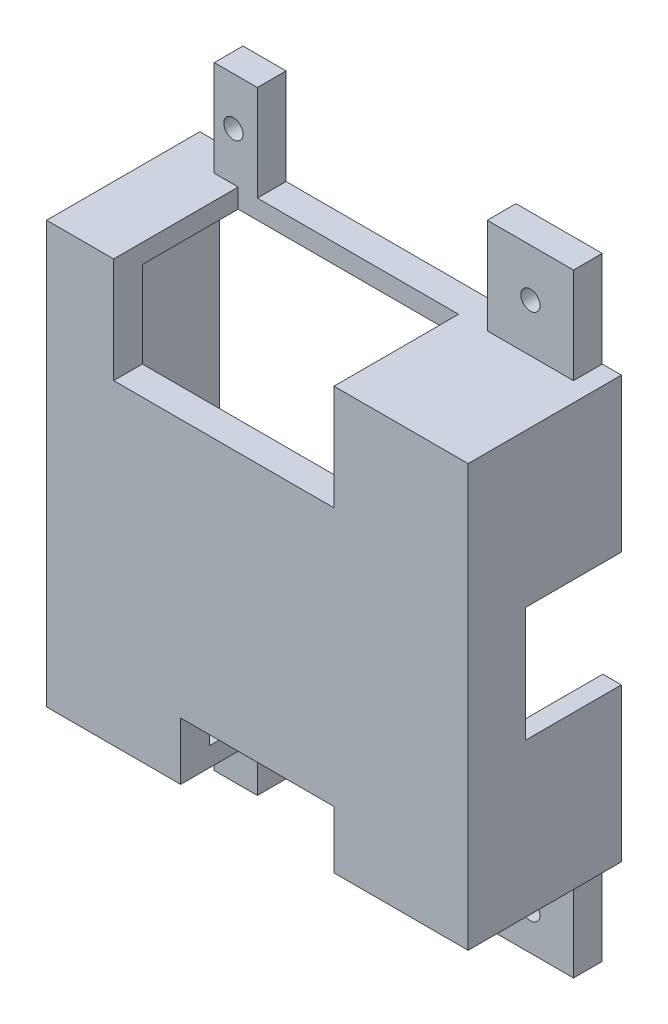
SolidWorks part; units mm, degrees
ref_plane "Front Plane" through (0, 0, 0) normal (0, 0, 1) x (1, 0, 0)
ref_plane "Top Plane" through (0, 0, 0) normal (0, 1, 0) x (1, 0, 0)
ref_plane "Right Plane" through (0, 0, 0) normal (1, 0, 0) x (0, 0, -1)
sketch "Sketch1" plane through (0, 0, 0) normal (0, 0, 1) x (1, 0, 0)
  line L0 (0, 0) -> (44, 0)
  line L1 (44, 0) -> (44, 44)
  line L2 (44, 44) -> (0, 44)
  line L3 (0, 44) -> (0, 0)
  dimension "D1" = 44
  dimension "D2" = 44
extrude "Boss-Extrude1" add sketch "Sketch1" along normal blind 16
sketch "Sketch3" plane through (0, 0, 0) normal (0, 0, -1) x (-1, 0, 0)
  line L1 (-42.0638, 42) -> (-2.0638, 42)
  line L2 (-42.0638, 42) -> (-42.0638, 2)
  line L3 (-42.0638, 2) -> (-2.0638, 2)
  line L4 (-2.0638, 42) -> (-2.0638, 2)
  dimension "D1" = 40
  dimension "D2" = 40
  dimension "D3" = 2
  dimension "D4" = 2
  dimension "D5" = 2
  dimension "D6" = 2
extrude "Cut-Extrude1" cut sketch "Sketch3" against normal blind 13
ref_plane "Plane1" through (0, 44, 16) normal (-1, 0, 0) x (0, 0, 1)
sketch "Sketch5" plane through (0, 0, 16) normal (0, 0, 1) x (1, 0, 0)
  line L0 (0, 44) -> (0, 0) construction
  line L1 (7, 44) -> (30, 44)
  line L2 (7, 44) -> (7, 33)
  line L3 (7, 33) -> (30, 33)
  line L4 (30, 44) -> (30, 33)
  dimension "D1" = 0
  dimension "D2" = 7
  dimension "D3" = 14
  dimension "D4" = 11
extrude "Cut-Extrude2" cut sketch "Sketch5" against normal blind 13
sketch "Sketch6" plane through (0, 0, 16) normal (0, 0, 1) x (1, 0, 0)
  line L0 (0, 0) -> (44, 0) construction
  line L1 (14, 6) -> (30, 6)
  line L2 (14, 6) -> (14, 0)
  line L3 (14, 0) -> (30, 0)
  line L4 (30, 6) -> (30, 0)
  dimension "D1" = 14
  dimension "D2" = 14
  dimension "D3" = 6
extrude "Cut-Extrude3" cut sketch "Sketch6" against normal blind 10
sketch "Sketch7" plane through (44, 0, 0) normal (1, 0, 0) x (0, 0, -1)
  line L0 (0, 0) -> (0, 44) construction
  line L1 (0, 16) -> (-10, 16)
  line L2 (0, 16) -> (0, 28)
  line L3 (0, 28) -> (-10, 28)
  line L4 (-10, 16) -> (-10, 28)
  dimension "D1" = 16
  dimension "D2" = 16
  dimension "D3" = 10
extrude "Cut-Extrude4" cut sketch "Sketch7" against normal blind 5
sketch "Sketch8" plane through (0, 0, 0) normal (0, -1, 0) x (-1, 0, 0)
  line L0 (0, 0) -> (-44, 0) construction
  line L1 (-4.5, -3) -> (-9, -3)
  line L2 (-4.5, -3) -> (-4.5, 0)
  line L3 (-4.5, 0) -> (-9, 0)
  line L4 (-9, -3) -> (-9, 0)
  line L6 (-33, -3) -> (-42, -3)
  line L7 (-33, -3) -> (-33, 0)
  line L8 (-33, 0) -> (-42, 0)
  line L9 (-42, -3) -> (-42, 0)
  dimension "D1" = 3
  dimension "D2" = 24
  dimension "D3" = 4.5
  dimension "D4" = 9
  dimension "D5" = 3
  dimension "D6" = 9
extrude "Boss-Extrude2" add sketch "Sketch8" along normal blind 10
sketch "Sketch9" plane through (0, 0, 3) normal (0, 0, 1) x (1, 0, 0)
  line L0 (33, -10) -> (33, 0) construction
  circle A0 centre (6.5, -6.0773) radius 1
  circle A1 centre (37.5, -6.0773) radius 1
  dimension "D2" = 2
  dimension "D3" = 2
  dimension "D1" = 31
  dimension "D4" = 4.5
extrude "Cut-Extrude5" cut sketch "Sketch9" against normal blind 10
sketch "Sketch10" plane through (0, 44, 0) normal (0, 1, 0) x (1, 0, 0)
  line L0 (44, 0) -> (0, 0) construction
  line L1 (42, 0) -> (33, 0)
  line L2 (42, 0) -> (42, -3)
  line L3 (42, -3) -> (33, -3)
  line L4 (33, 0) -> (33, -3)
  line L6 (9, 0) -> (4.5, 0)
  line L7 (9, 0) -> (9, -3)
  line L8 (9, -3) -> (4.5, -3)
  line L9 (4.5, 0) -> (4.5, -3)
  dimension "D1" = 3
  dimension "D2" = 3
  dimension "D3" = 9
  dimension "D4" = 24
  dimension "D5" = 4.5
  dimension "D6" = 9
extrude "Boss-Extrude3" add sketch "Sketch10" along normal blind 10
sketch "Sketch11" plane through (0, 0, 3) normal (0, 0, 1) x (1, 0, 0)
  line L0 (42, 54) -> (42, 44) construction
  circle A0 centre (37.5, 49.0313) radius 1
  circle A1 centre (6.5, 49.0313) radius 1
  dimension "D3" = 2
  dimension "D4" = 2
  dimension "D1" = 31
  dimension "D2" = 4.5
extrude "Cut-Extrude6" cut sketch "Sketch11" against normal blind 10
